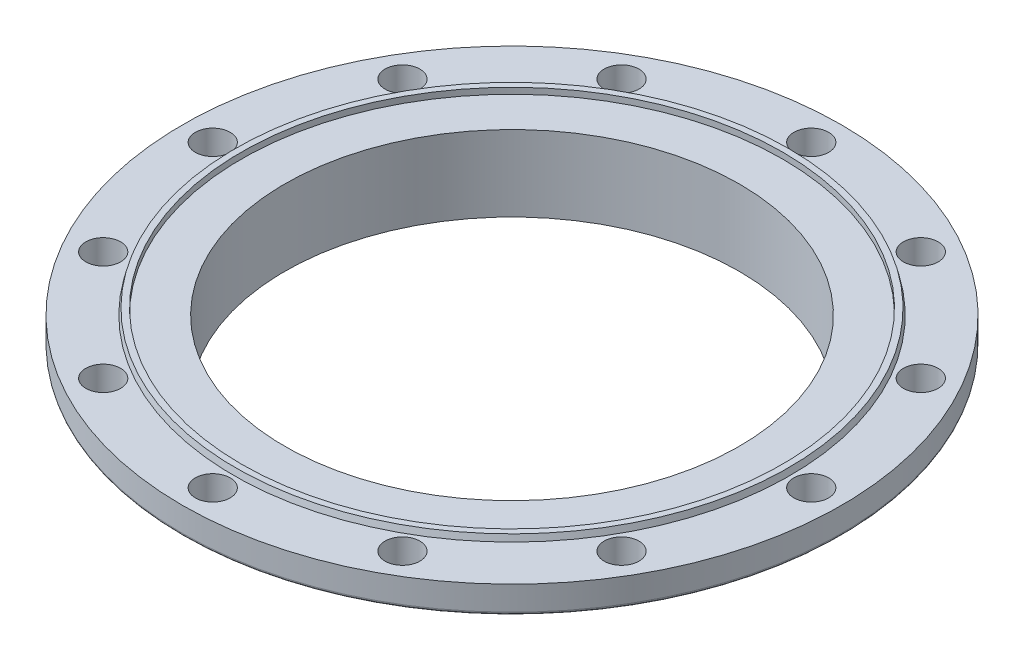
SolidWorks part; units mm, degrees
material " 12Х18Н10Т ГОСТ 4543-71"
ref_plane "Спереди" through (0, 0, 0) normal (0, 0, 1) x (1, 0, 0)
ref_plane "Сверху" through (0, 0, 0) normal (0, 1, 0) x (1, 0, 0)
ref_plane "Справа" through (0, 0, 0) normal (1, 0, 0) x (0, 0, -1)
sketch "Эскиз1" plane through (0, 0, 0) normal (0, 0, 1) x (1, 0, 0)
  line L0 (0, 0) -> (0, 60.5833) construction
  line L1 (-150, 0) -> (-150, 50)
  line L2 (-150, 50) -> (-178.5, 50)
  line L3 (-178.5, 50) -> (-178.5, 54)
  line L4 (-178.5, 54) -> (-182.5, 54)
  line L5 (-182.5, 54) -> (-183.5, 50)
  line L6 (-183.5, 50) -> (-217.5, 50)
  line L7 (-217.5, 50) -> (-217.5, 34)
  line L8 (-215.5, 32) -> (-175.9912, 32)
  line L9 (-169.0751, 26.0806) -> (-165, 0)
  line L10 (-165, 0) -> (-150, 0)
  arc A0 (-169.0751, 26.0806) -> (-175.9912, 32) centre (-175.9912, 25) ccw
  arc A1 (-217.5, 34) -> (-215.5, 32) centre (-215.5, 34) ccw
  point P15 (-170, 32)
  dimension "D12" = 7
  dimension "D13" = 2
  dimension "D1" = 435
  dimension "D2" = 300
  dimension "D3" = 330
  dimension "D4" = 340
  dimension "D5" = 54
  dimension "D6" = 365
  dimension "D7" = 357
  dimension "D8" = 18
  dimension "D9" = 4
  dimension "D10" = 4
  dimension "D11" = 1
revolve "Повернуть1" add sketch "Эскиз1" angle 360 about L0
sketch "Эскиз2" plane through (0, 50, 0) normal (0, 1, 0) x (1, 0, 0)
  circle A0 centre (0, 0) radius 197.5 construction
  circle A1 centre (-197.5, 0) radius 11.5
  circle A2 centre (-171.04, 98.75) radius 11.5
  circle A3 centre (-98.75, 171.04) radius 11.5
  circle A4 centre (0, 197.5) radius 11.5
  circle A5 centre (98.75, 171.04) radius 11.5
  circle A6 centre (171.04, 98.75) radius 11.5
  circle A7 centre (197.5, 0) radius 11.5
  circle A8 centre (171.04, -98.75) radius 11.5
  circle A9 centre (98.75, -171.04) radius 11.5
  circle A10 centre (0, -197.5) radius 11.5
  circle A11 centre (-98.75, -171.04) radius 11.5
  circle A12 centre (-171.04, -98.75) radius 11.5
  point P14 (0, 0)
  dimension "D1" = 395
  dimension "D2" = 23
  dimension "D3" = 12
extrude "Вырез-Вытянуть1" cut sketch "Эскиз2" against normal through all
